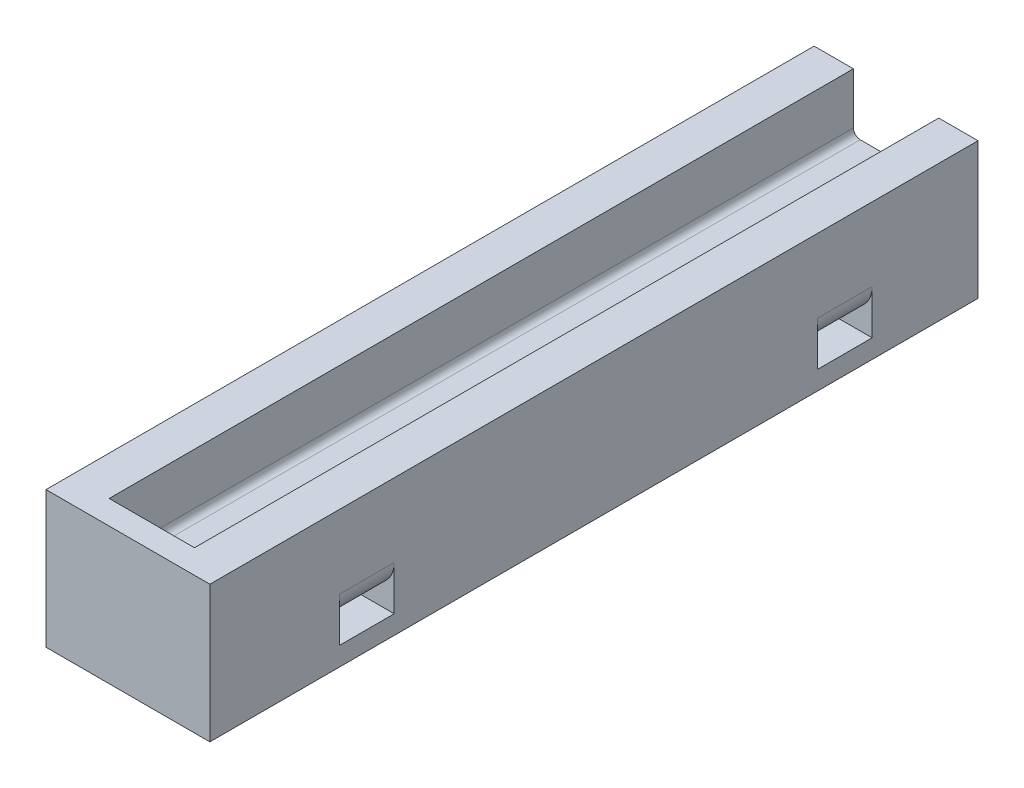
SolidWorks part; units mm, degrees
material "PLA"
ref_plane "Front Plane" through (0, 0, 0) normal (0, 0, 1) x (1, 0, 0)
ref_plane "Top Plane" through (0, 0, 0) normal (0, 1, 0) x (1, 0, 0)
ref_plane "Right Plane" through (0, 0, 0) normal (1, 0, 0) x (0, 0, -1)
sketch "Sketch1" plane through (0, 0, 0) normal (0, 0, 1) x (1, 0, 0)
  line L0 (-36, 5.6) -> (-26, 5.6) construction
  line L1 (-31, 5.6) -> (-31, 5.75) construction
  line L2 (0, 0) -> (-320, 0) construction
  line L3 (-37.25, 11.5) -> (-24.75, 11.5)
  line L4 (-37.25, 11.5) -> (-37.25, 0)
  line L5 (-37.25, 0) -> (-24.75, 0)
  line L6 (-24.75, 11.5) -> (-24.75, 0)
  line L7 (-37.25, 11.5) -> (-24.75, 0) construction
  line L8 (-37.25, 0) -> (-24.75, 11.5) construction
  line L10 (-24.75, 0) -> (-19, 0)
  line L11 (-24.75, 0) -> (-24.75, 20)
  line L12 (-24.75, 20) -> (-19, 20)
  line L13 (-19, 0) -> (-19, 20)
  line L14 (-37.25, 0) -> (-43, 0)
  line L15 (-37.25, 0) -> (-37.25, 20)
  line L16 (-37.25, 20) -> (-43, 20)
  line L17 (-43, 0) -> (-43, 20)
  dimension "D1" = 24
  dimension "D2" = 12.5
  dimension "D3" = 11.5
  dimension "D4" = 20
extrude "Boss-Extrude1" add sketch "Sketch1" along normal blind 109 contours L17 L14 L4 L15 L16 | L6 L3 L4 L5 | L10 L13 L12 L11 L6
sketch "Sketch2" plane through (0, 0, 109) normal (0, 0, 1) x (1, 0, 0)
  line L1 (-43, 20) -> (-19, 20)
  line L2 (-43, 20) -> (-43, 0)
  line L3 (-43, 0) -> (-19, 0)
  line L4 (-19, 20) -> (-19, 0)
extrude "Boss-Extrude2" add sketch "Sketch2" along normal blind 3.5
sketch "Sketch3" plane through (0, 0, 0) normal (0, 0, -1) x (-1, 0, 0)
  circle A0 centre (26, 5.6) radius 1.45 construction
  circle A1 centre (26, 5.6) radius 1.45 construction
  circle A2 centre (36, 5.6) radius 1.45 construction
  circle A3 centre (36, 5.6) radius 1.45 construction
  point P7 (26, 5.6)
  point P8 (36, 5.6)
hole_wizard "Ø2.5mm Dowel Hole1" positions "Sketch3" profile "Sketch4" hole size "Ø2.5" standard "ANSI Metric"
sketch "Sketch4" plane through (-36, 5.6, 0) normal (1, 0, 0) x (0, 1, 0)
  line L0 (0, 0) -> (0, 7.4614)
  line L1 (0, 7.4614) -> (1.6, 6.5)
  line L2 (1.6, 6.5) -> (1.6, 0)
  line L5 (1.6, 0) -> (0, 0)
  line L10 (0, 7.4614) -> (-1.6, 6.5) construction
  line L11 (0, -6.35) -> (0, 107.95) construction
  dimension "Hole Dia." = 3.2
  dimension "Hole Depth" = 6.5
  dimension "Drill Angle" = 118
sketch "Sketch5" plane through (-19, 0, 0) normal (1, 0, 0) x (0, 0, -1)
  line L0 (-109, 11.5) -> (-109, 20) construction
  line L1 (-109, 0) -> (-109, 20) construction
  line L2 (-112.5, 0) -> (0, 0) construction
  line L4 (-109, 4) -> (-89.5, 4) construction
  line L5 (-89.5, 4) -> (-19.5, 4) construction
  line L6 (-19.5, 4) -> (0, 4) construction
  line L7 (0, 0) -> (0, 20) construction
  line L9 (-93.5, 2.75) -> (-85.5, 2.75)
  line L10 (-93.5, 2.75) -> (-93.5, 5.25)
  line L11 (-93.5, 5.25) -> (-85.5, 5.25)
  line L12 (-85.5, 2.75) -> (-85.5, 5.25)
  line L13 (-93.5, 2.75) -> (-85.5, 5.25) construction
  line L14 (-93.5, 5.25) -> (-85.5, 2.75) construction
  line L15 (-15.5, 2.75) -> (-23.5, 2.75)
  line L16 (-15.5, 2.75) -> (-15.5, 5.25)
  line L17 (-15.5, 5.25) -> (-23.5, 5.25)
  line L18 (-23.5, 2.75) -> (-23.5, 5.25)
  line L19 (-15.5, 2.75) -> (-23.5, 5.25) construction
  line L20 (-15.5, 5.25) -> (-23.5, 2.75) construction
  dimension "D1" = 70
  dimension "D2" = 4
  dimension "D3" = 2.5
  dimension "D4" = 8
extrude "Cut-Extrude1" cut sketch "Sketch5" against normal through all
fillet "Fillet1" radius 4 4 edges at (-43, 5.25, 19.5) (-43, 5.25, 89.5) (-19, 5.25, 19.5) (-19, 5.25, 89.5)
chamfer "Chamfer1" distance 0.5 angle 45 2 edges at (-37.6, 5.6, 0) (-27.6, 5.6, 0)
fillet "Fillet2" radius 1 2 edges at (-37.25, 11.5, 54.5) (-24.75, 11.5, 54.5)
